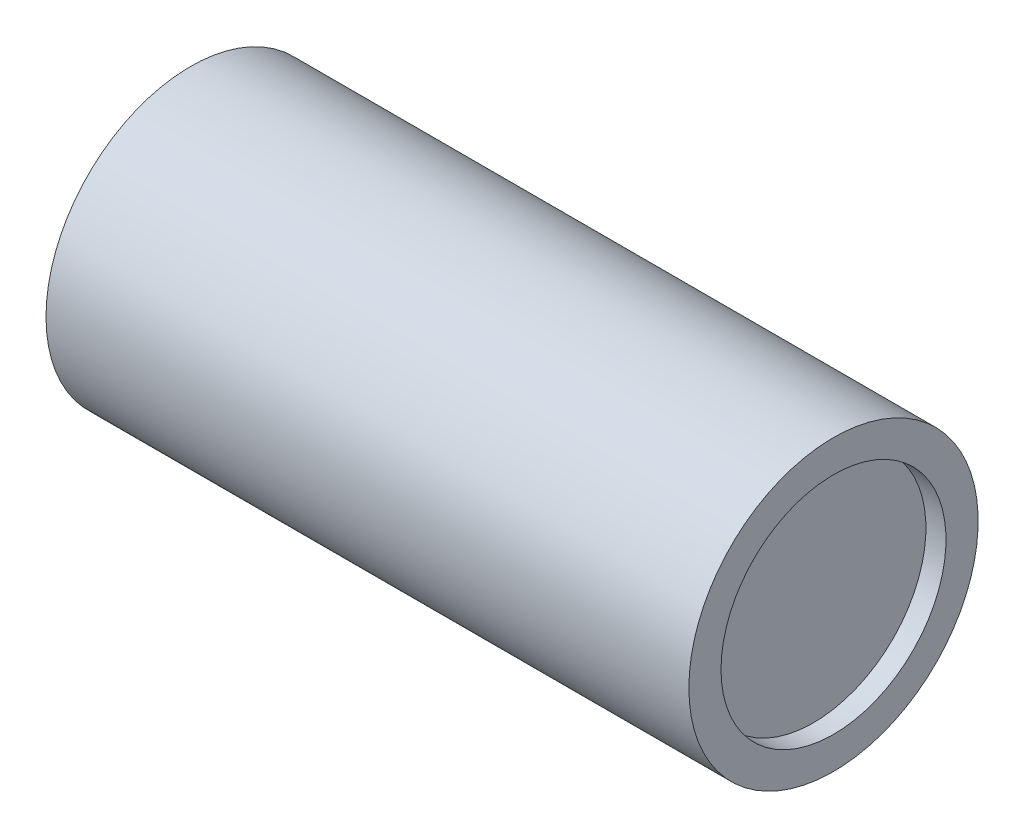
SolidWorks part; units mm, degrees
ref_plane "Front Plane" through (0, 0, 0) normal (0, 0, 1) x (1, 0, 0)
ref_plane "Top Plane" through (0, 0, 0) normal (0, 1, 0) x (1, 0, 0)
ref_plane "Right Plane" through (0, 0, 0) normal (1, 0, 0) x (0, 0, -1)
sketch "Sketch4" plane through (0, 0, 0) normal (0, 0, 1) x (1, 0, 0)
  line L0 (0, 0) -> (0, 8.89)
  line L1 (0, 8.89) -> (-1.5875, 8.89)
  line L2 (-1.5875, 8.89) -> (-1.5875, 11.43)
  line L3 (-1.5875, 11.43) -> (49.2125, 11.43)
  line L4 (49.2125, 11.43) -> (49.2125, 8.89)
  line L5 (49.2125, 8.89) -> (47.625, 8.89)
  line L6 (47.625, 8.89) -> (47.625, 0)
  line L7 (0, 0) -> (1.5875, 0)
  line L8 (1.5875, 0) -> (1.5875, 8.89)
  line L9 (1.5875, 8.89) -> (46.0375, 8.89)
  line L10 (46.0375, 8.89) -> (46.0375, 0)
  line L11 (46.0375, 0) -> (47.625, 0)
  dimension "D1" = 8.89
  dimension "D2" = 1.5875
  dimension "D3" = 2.54
  dimension "D4" = 50.8
  dimension "D5" = 1.5875
  dimension "D6" = 1.5875
  dimension "D7" = 1.5875
revolve "Revolve1" add sketch "Sketch4" angle 360 about L7
